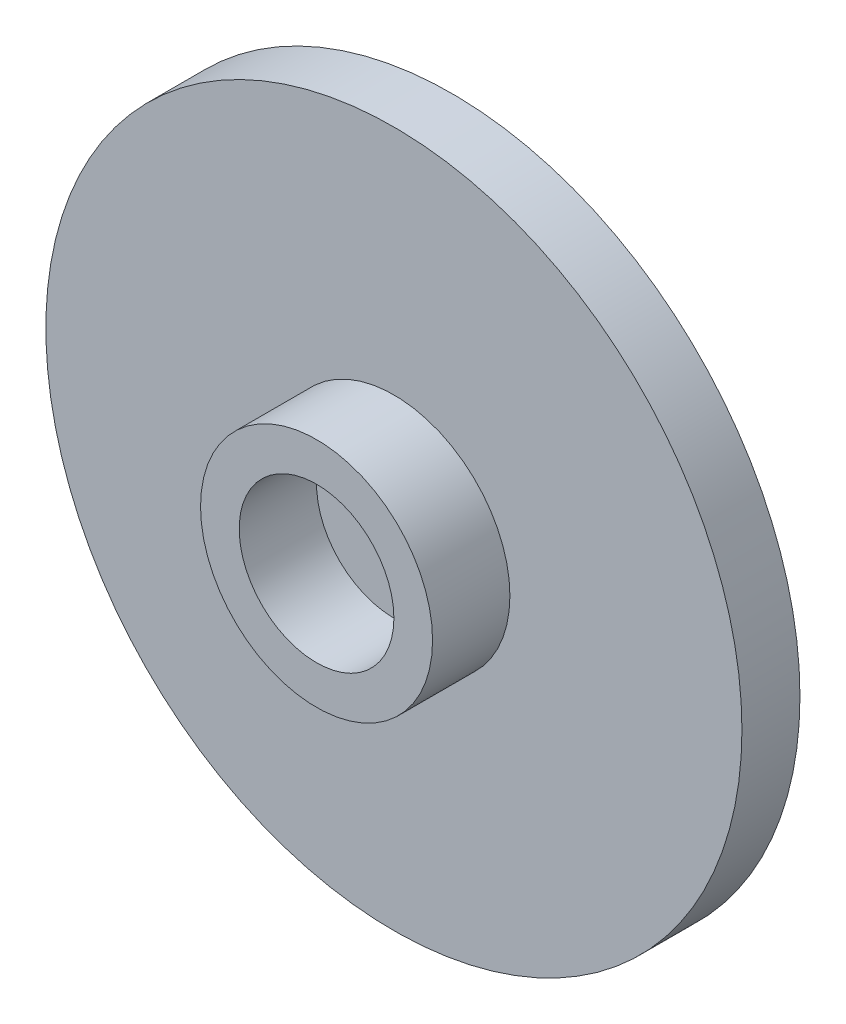
SolidWorks part; units mm, degrees
ref_plane "前视基准面" through (0, 0, 0) normal (0, 0, 1) x (1, 0, 0)
ref_plane "上视基准面" through (0, 0, 0) normal (0, 1, 0) x (1, 0, 0)
ref_plane "右视基准面" through (0, 0, 0) normal (1, 0, 0) x (0, 0, -1)
sketch "草图1" plane through (0, 0, 0) normal (0, 0, 1) x (1, 0, 0)
  circle A0 centre (0, 0) radius 9
  circle A1 centre (0, 0) radius 0.75
extrude "凸台-拉伸1" add sketch "草图1" along normal blind 1.5
sketch "草图2" plane through (0, 0, 1.5) normal (0, 0, 1) x (1, 0, 0)
  circle A0 centre (0, 0) radius 3
  circle A1 centre (0, 0) radius 2
extrude "凸台-拉伸2" add sketch "草图2" along normal blind 2
sketch "草图3" plane through (0, 0, 0) normal (0, 0, -1) x (-1, 0, 0)
  circle A0 centre (0, 0) radius 3
  circle A1 centre (0, 0) radius 2
extrude "凸台-拉伸3" add sketch "草图3" along normal blind 1
